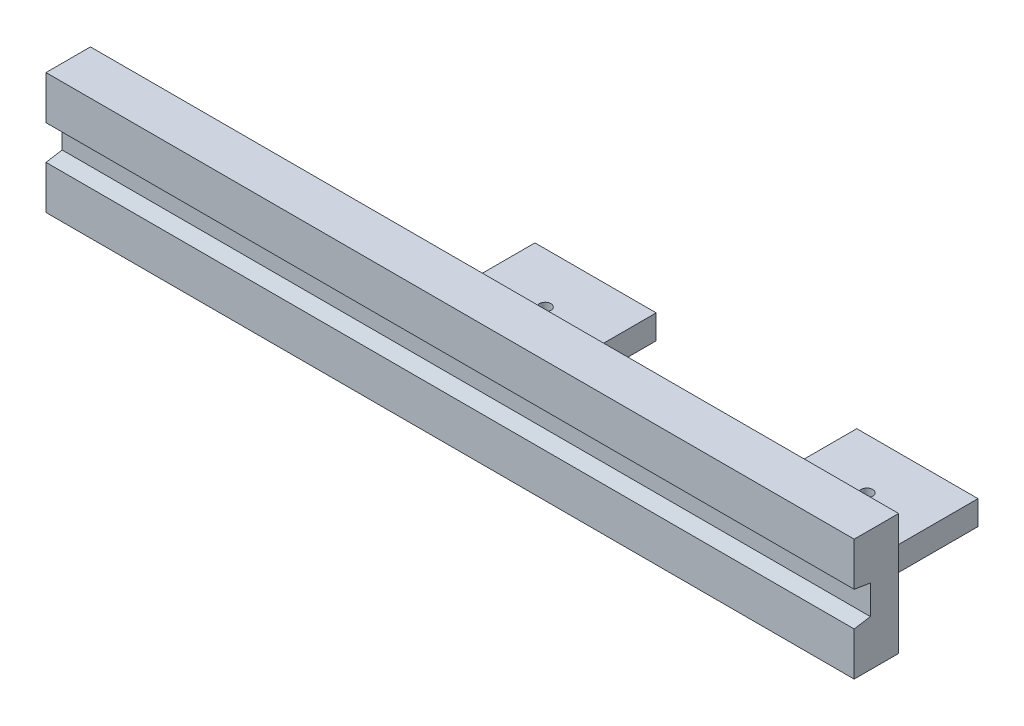
SolidWorks part; units mm, degrees
ref_plane "前基準面" through (0, 0, 0) normal (0, 0, 1) x (1, 0, 0)
ref_plane "上基準面" through (0, 0, 0) normal (0, 1, 0) x (1, 0, 0)
ref_plane "右基準面" through (0, 0, 0) normal (1, 0, 0) x (0, 0, -1)
sketch "草圖1" plane through (0, 0, 0) normal (0, 0, 1) x (1, 0, 0)
  line L0 (0, 0) -> (200, 0)
  line L1 (200, 0) -> (200, 30)
  line L2 (200, 30) -> (0, 30)
  line L3 (0, 30) -> (0, 0)
  dimension "D1" = 30
  dimension "D2" = 200
extrude "填料-伸長1" add sketch "草圖1" along normal blind 11
sketch "草圖4" plane through (0, 0, 0) normal (0, 0, -1) x (-1, 0, 0)
  line L0 (-200, 15) -> (0, 15)
  line L1 (-200, 0) -> (-200, 30) construction
  line L2 (0, 30) -> (0, 0) construction
  line L3 (-100, 30) -> (-100, 0)
  line L4 (-200, 30) -> (0, 30) construction
  line L5 (0, 0) -> (-200, 0) construction
  line L6 (-115, 15) -> (-100, 15)
  line L7 (-100, 15) -> (-85, 15)
  line L8 (-115, 15) -> (-115, 18)
  line L9 (-115, 18) -> (-85, 18)
  line L10 (-85, 18) -> (-85, 15)
  line L11 (-115, 15) -> (-115, 12)
  line L12 (-115, 12) -> (-100, 12)
  line L13 (-100, 12) -> (-85, 12)
  line L14 (-85, 12) -> (-85, 15)
  line L16 (-164.6389, 12) -> (-194.6389, 12)
  line L17 (-164.6389, 12) -> (-164.6389, 18)
  line L18 (-164.6389, 18) -> (-194.6389, 18)
  line L19 (-194.6389, 12) -> (-194.6389, 18)
  line L20 (-164.6389, 12) -> (-194.6389, 18) construction
  line L21 (-164.6389, 18) -> (-194.6389, 12) construction
  point P17 (-179.6389, 15)
  dimension "D1" = 15
  dimension "D2" = 15
  dimension "D3" = 3
  dimension "D4" = 3
  dimension "D5" = 6
  dimension "D6" = 30
extrude "填料-伸長2" add sketch "草圖4" along normal blind 25 contours L11 L12 L3 L0 | L9 L8 L0 L3 | L10 L9 L3 L0 | L13 L14 L0 L3
sketch "草圖5" plane through (200, 0, 0) normal (1, 0, 0) x (0, 0, -1)
  line L0 (-11, 30) -> (-11, 19.25)
  line L1 (-11, 0) -> (-11, 30) construction
  line L2 (-7, 15) -> (-7, 11.402)
  line L3 (-7, 15) -> (-7, 18.6)
  line L4 (-7, 18.6) -> (-11, 19.25)
  line L5 (-11, 10.75) -> (-11, 0)
  line L6 (-11, 15) -> (0, 15)
  line L7 (0, 30) -> (0, 0) construction
  line L8 (-7, 11.402) -> (-11, 10.75)
  line L9 (-11, 10.75) -> (-11, 19.25)
  line M6 (-11, 30) -> (-11, 0)
  dimension "D1" = 8.5
  dimension "D2" = 10.75
  dimension "D3" = 10.75
  dimension "D4" = 3.6
  dimension "D5" = 3.598
  dimension "D6" = 4
extrude "除料-伸長2" cut sketch "草圖5" against normal through all contours L6 L3 L4 M6 | L8 L2 L6 M6
sketch "草圖6" plane through (0, 12, 0) normal (0, -1, 0) x (1, 0, 0)
  line L0 (100, 0) -> (100, -25)
  line L1 (200, 0) -> (0, 0) construction
  line L2 (115, -25) -> (85, -25) construction
  line L3 (85, -12.5) -> (115, -12.5)
  line L4 (85, -25) -> (85, 0) construction
  line L5 (115, -25) -> (115, 0) construction
  circle A0 centre (100, -12.5) radius 1.45
extrude "除料-伸長3" cut sketch "草圖6" against normal through all contours L3 A0 L0 | L0 A0 L3 | L3 A0 L0 | L0 A0 L3
sketch "草圖7" plane through (0, 12, 0) normal (0, -1, 0) x (1, 0, 0)
  line L0 (100, -13.95) -> (100, -25)
  line L1 (115, -25) -> (85, -25) construction
  circle A0 centre (100, -12.5) radius 1.45 construction
sketch "草圖9" plane through (0, 0, 0) normal (0, 0, -1) x (-1, 0, 0)
  line L1 (-194.6389, 18) -> (-164.6389, 18)
  line L2 (-194.6389, 18) -> (-194.6389, 12)
  line L3 (-194.6389, 12) -> (-164.6389, 12)
  line L4 (-164.6389, 18) -> (-164.6389, 12)
  line L5 (-194.6389, 18) -> (-164.6389, 12) construction
  line L6 (-194.6389, 12) -> (-164.6389, 18) construction
  point P0 (-179.6389, 15)
extrude "填料-伸長3" add sketch "草圖9" along normal blind 25
sketch "草圖10" plane through (0, 18, 0) normal (0, 1, 0) x (1, 0, 0)
  line L0 (194.6389, 12.5) -> (164.6389, 12.5)
  line L1 (194.6389, 25) -> (194.6389, 0) construction
  line L2 (164.6389, 25) -> (164.6389, 0) construction
  circle A0 centre (179.6389, 12.5) radius 1.45
  dimension "D1" = 2.9
extrude "除料-伸長4" cut sketch "草圖10" against normal through all contours L0 A0 | L0 A0
